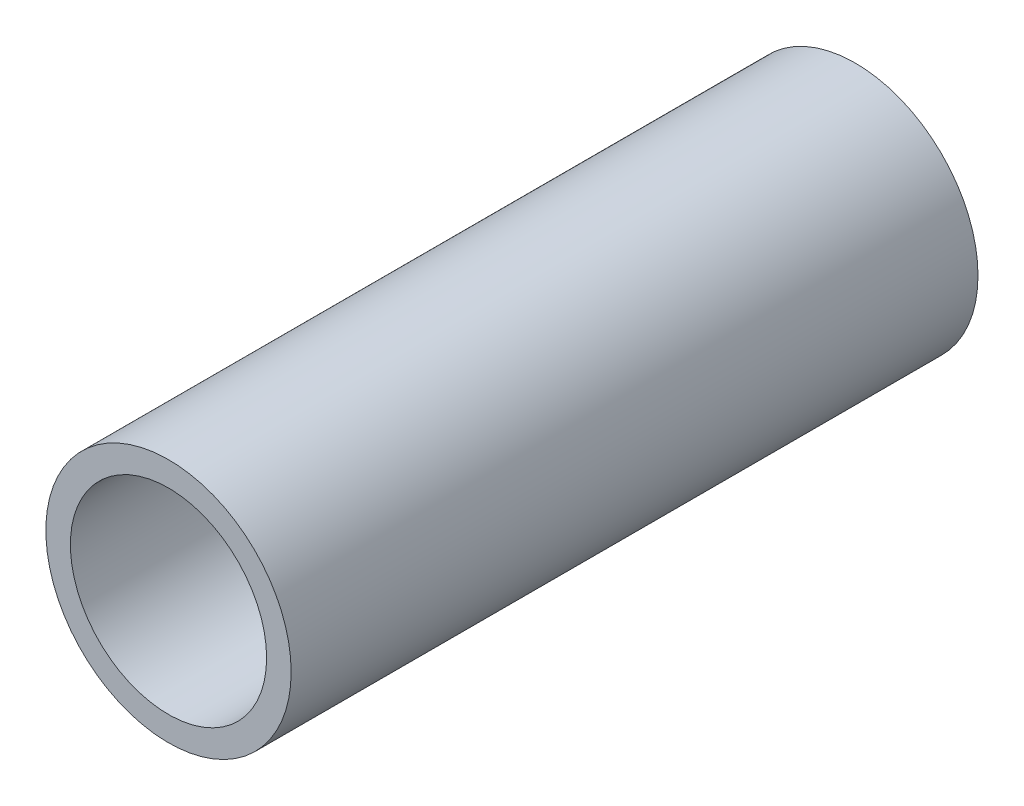
SolidWorks part; units mm, degrees
ref_plane "Front Plane" through (0, 0, 0) normal (0, 0, 1) x (1, 0, 0)
ref_plane "Top Plane" through (0, 0, 0) normal (0, 1, 0) x (1, 0, 0)
ref_plane "Right Plane" through (0, 0, 0) normal (1, 0, 0) x (0, 0, -1)
sketch "Sketch1" plane through (0, 0, 0) normal (0, 0, 1) x (1, 0, 0)
  circle A0 centre (0, 0) radius 50
  dimension "D1" = 100
extrude "Boss-Extrude1" add sketch "Sketch1" along normal blind 280
shell "Shell3" thickness 10
